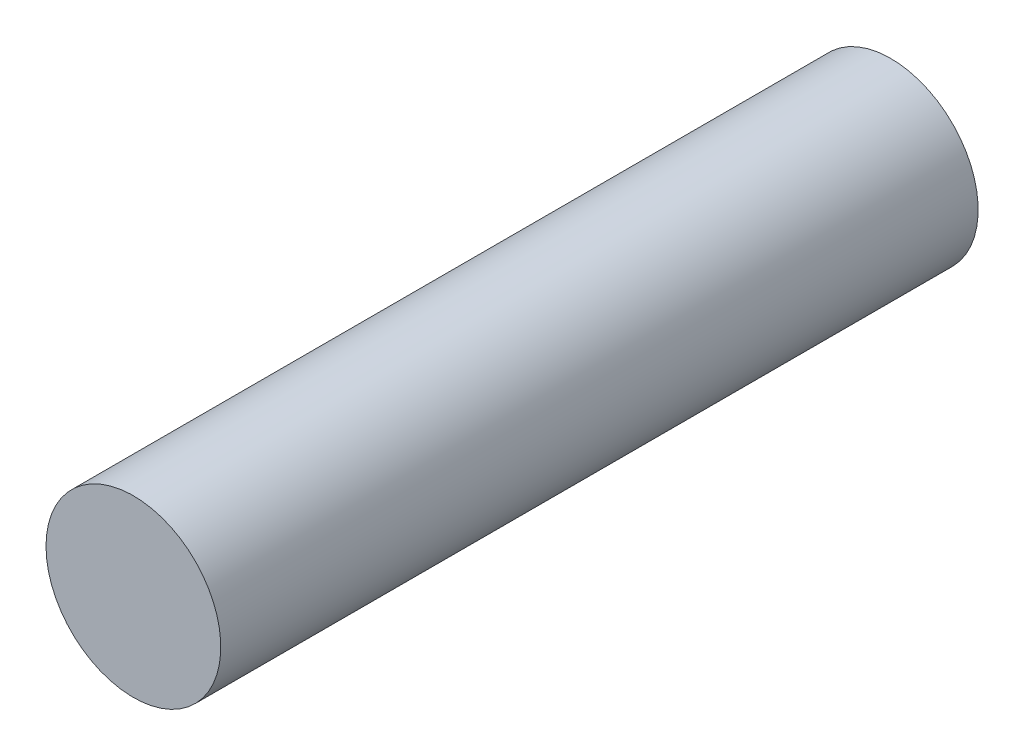
SolidWorks part; units mm, degrees
ref_plane "정면" through (0, 0, 0) normal (0, 0, 1) x (1, 0, 0)
ref_plane "윗면" through (0, 0, 0) normal (0, 1, 0) x (1, 0, 0)
ref_plane "우측면" through (0, 0, 0) normal (1, 0, 0) x (0, 0, -1)
sketch "스케치1" plane through (0, 0, 0) normal (0, 0, 1) x (1, 0, 0)
  circle A0 centre (0, 0) radius 3
  dimension "D1" = 6
extrude "보스-돌출1" add sketch "스케치1" along normal blind 26
